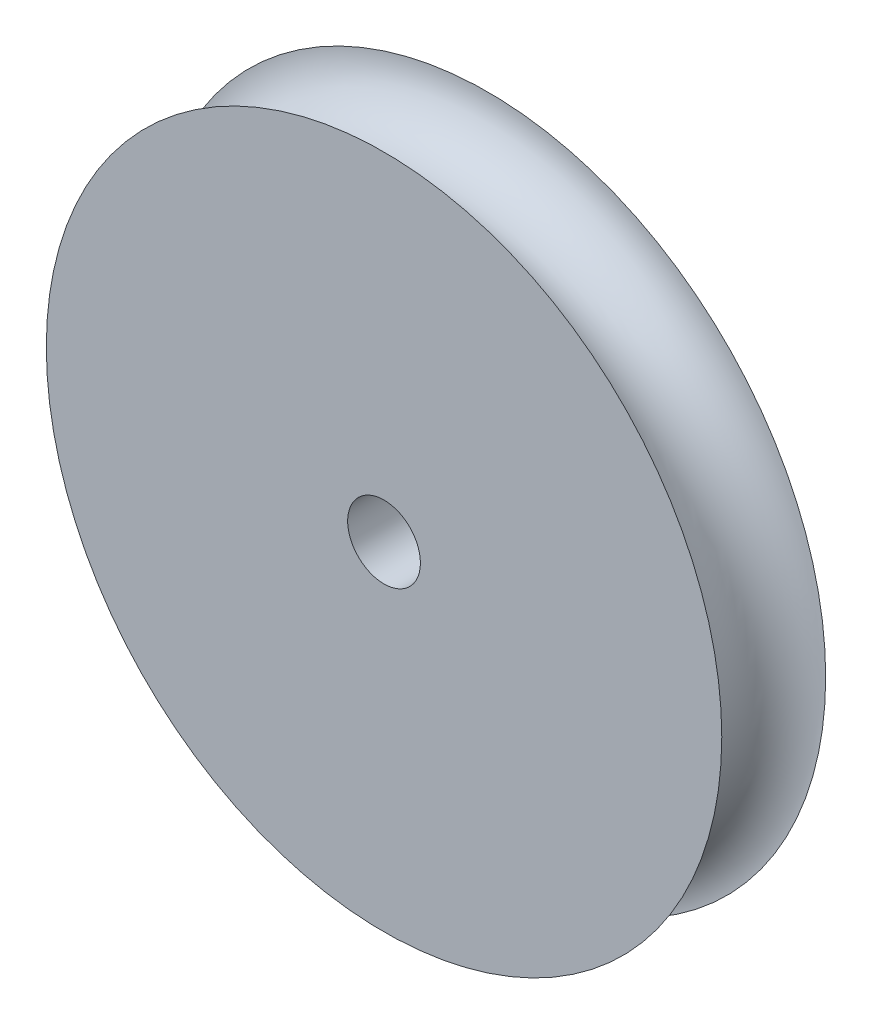
SolidWorks part; units mm, degrees
ref_plane "Front Plane" through (0, 0, 0) normal (0, 0, 1) x (1, 0, 0)
ref_plane "Top Plane" through (0, 0, 0) normal (0, 1, 0) x (1, 0, 0)
ref_plane "Right Plane" through (0, 0, 0) normal (1, 0, 0) x (0, 0, -1)
sketch "Sketch2" plane through (-159.0697, 156.2968, 0) normal (-0.7133, 0.7009, 0) x (0, 0, 1)
  line L0 (0, 318.5) -> (0, 311.5) construction
  line L4 (0, 315) -> (29.0274, 315) construction
  line L6 (29.0274, 315) -> (19.0274, 315)
  line L7 (29.0274, 315) -> (29.0274, 347.5)
  line L8 (29.0274, 347.5) -> (19.0274, 347.5) construction
  line L9 (19.0274, 315) -> (19.0274, 347.5)
  circle A0 centre (24.0274, 347.5) radius 5 construction
  arc A1 (19.0274, 347.5) -> (29.0274, 347.5) centre (24.0274, 347.5) ccw
  dimension "D1" = 32.5
  dimension "D2" = 10
revolve "Revolve1" add sketch "Sketch2" angle 360 about L6
sketch "Sketch3" plane through (0, 0, 29.0274) normal (0, 0, 1) x (1, 0, 0)
  circle A0 centre (61.702, 380.9852) radius 3.5
  dimension "D1" = 7
extrude "Cut-Extrude1" cut sketch "Sketch3" against normal through all
